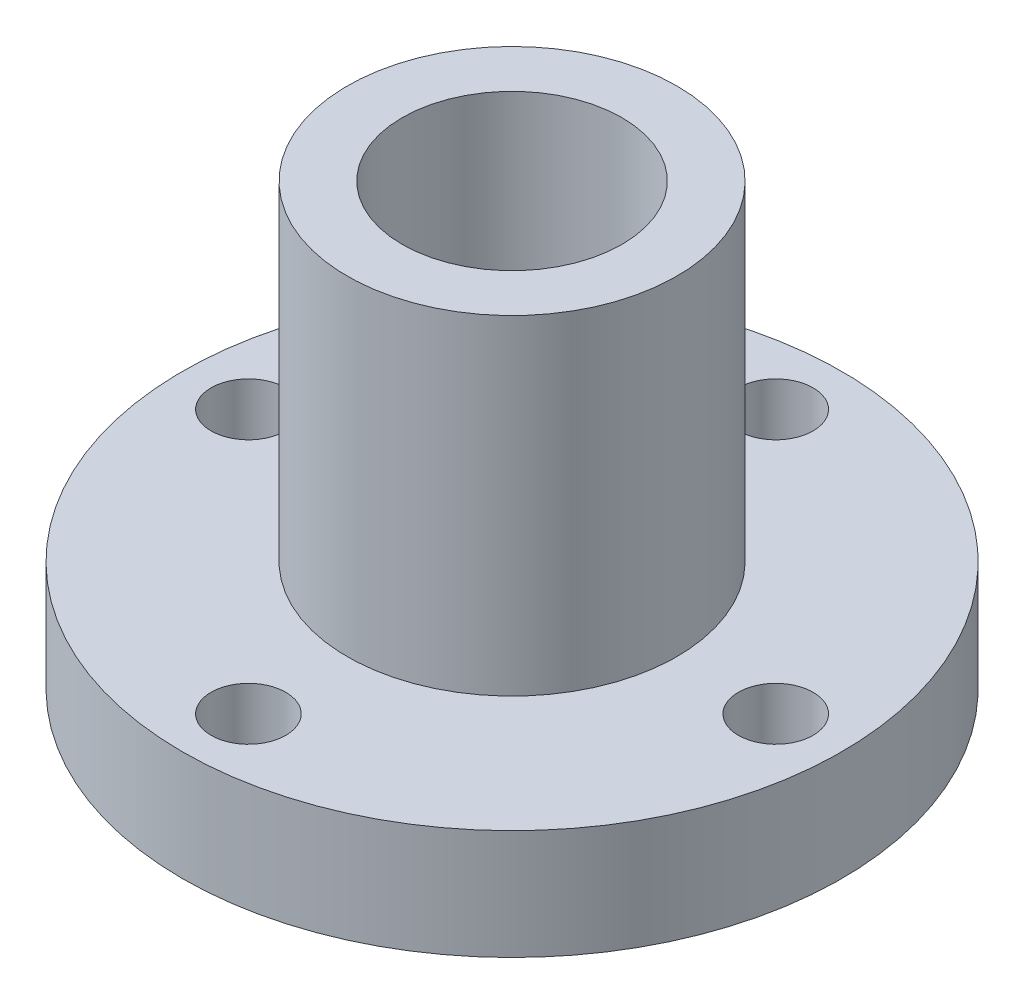
SolidWorks part; units mm, degrees
ref_plane "Front Plane" through (0, 0, 0) normal (0, 0, 1) x (1, 0, 0)
ref_plane "Top Plane" through (0, 0, 0) normal (0, 1, 0) x (1, 0, 0)
ref_plane "Right Plane" through (0, 0, 0) normal (1, 0, 0) x (0, 0, -1)
sketch "Sketch1" plane through (0, 0, 0) normal (0, 1, 0) x (1, 0, 0)
  circle A0 centre (0, 0) radius 19.05
  circle A1 centre (0, 0) radius 6.35
extrude "Boss-Extrude1" add sketch "Sketch1" along normal blind 6.35
sketch "Sketch2" plane through (0, 6.35, 0) normal (0, 1, 0) x (1, 0, 0)
  circle A0 centre (0, 0) radius 9.525
  circle A1 centre (0, 0) radius 6.35
extrude "Boss-Extrude2" add sketch "Sketch2" along normal blind 19.05
sketch "Sketch3" plane through (0, 6.35, 0) normal (0, 1, 0) x (1, 0, 0)
  circle A0 centre (0, 0) radius 15.24 construction
  circle A1 centre (0, 15.24) radius 2.159
  circle A2 centre (15.24, 0) radius 2.159
  circle A3 centre (0, -15.24) radius 2.159
  circle A4 centre (-15.24, 0) radius 2.159
extrude "Cut-Extrude1" cut sketch "Sketch3" against normal blind 11.938
